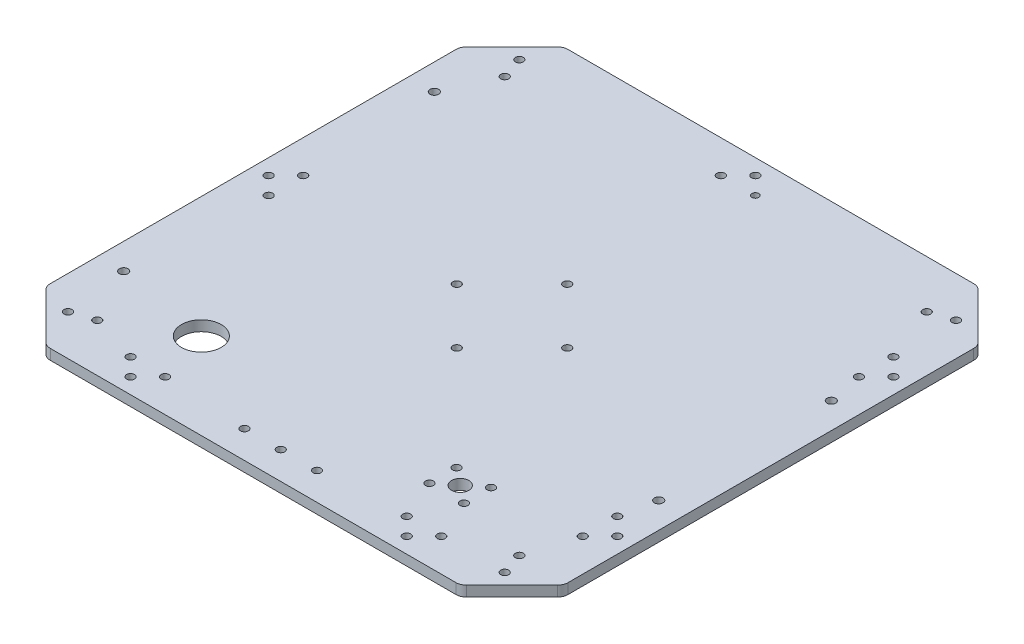
SolidWorks part; units mm, degrees
ref_plane "Plan de face" through (0, 0, 0) normal (0, 0, 1) x (1, 0, 0)
ref_plane "Plan de dessus" through (0, 0, 0) normal (0, 1, 0) x (1, 0, 0)
ref_plane "Plan de droite" through (0, 0, 0) normal (1, 0, 0) x (0, 0, -1)
sketch "Esquisse1" plane through (0, 0, 0) normal (0, 1, 0) x (1, 0, 0)
  line L0 (150, -150) -> (150, 150) construction
  line L1 (150, 150) -> (0, 150) construction
  line L2 (-150, 150) -> (-150, -150) construction
  line L3 (-150, 150) -> (150, 150) construction
  line L4 (150, 0) -> (-150, 0) construction
  line L5 (150, -150) -> (-150, -150) construction
  line L6 (0, 150) -> (0, -150) construction
  line L7 (-150, 0) -> (-150, 120)
  line L8 (0, 150) -> (-120, 150)
  line L9 (-150, 120) -> (-120, 150)
  line L10 (0, 150) -> (120, 150)
  line L11 (150, 0) -> (150, 120)
  line L12 (150, 120) -> (120, 150)
  line L13 (-150, 0) -> (-150, -120)
  line L14 (0, -150) -> (-120, -150)
  line L15 (-120, -150) -> (-150, -120)
  line L16 (150, 0) -> (150, -120)
  line L17 (0, -150) -> (120, -150)
  line L18 (120, -150) -> (150, -120)
  dimension "D1" = 42.4264
  dimension "D2" = 240
extrude "Boss.-Extru.1" add sketch "Esquisse1" along normal blind 6
fillet "Congé3" radius 6 8 edges at (150, 3, -120) (120, 3, -150) (-120, 3, -150) (-150, 3, -120) (-150, 3, 120) (-120, 3, 150) (120, 3, 150) (150, 3, 120)
sketch "Esquisse10" plane through (0, 6, 0) normal (0, 1, 0) x (1, 0, 0)
  line L0 (150, -100) -> (150, 100) construction
  line L1 (150, -117.5147) -> (150, 117.5147) construction
  line L2 (150, 100) -> (-80, 100) construction
  line L3 (-3.3, 0) -> (3.3, 0) construction
  line L4 (150, -100) -> (-80, -100) construction
  circle A0 centre (-80, 100) radius 11.5 construction
  circle A1 centre (-80, -100) radius 11.5
  point P10 (150, 0)
  dimension "D1" = 100
extrude "Enlèv. mat.-Extru.9" cut sketch "Esquisse10" against normal up to next
sketch "Esquisse11" plane through (0, 6, 0) normal (0, 1, 0) x (1, 0, 0)
  line L0 (0, 0) -> (70, 0) construction
  line L1 (70, 100) -> (70, -100) construction
  line L2 (-3.3, 0) -> (3.3, 0) construction
  line L3 (70, -100) -> (80, -100) construction
  line L4 (80, -92.15) -> (80, -107.85) construction
  line L5 (60, -92.15) -> (60, -107.85) construction
  circle A0 centre (70, -100) radius 5
  circle A1 centre (70, 100) radius 5 construction
  circle A2 centre (80, -107.85) radius 2.3
  circle A3 centre (80, -92.15) radius 2.3
  circle A4 centre (60, -92.15) radius 2.3
  circle A5 centre (60, -107.85) radius 2.3
  dimension "D1" = 100
  dimension "D2" = 7.85
  dimension "D3" = 10
extrude "Enlèv. mat.-Extru.10" cut sketch "Esquisse11" against normal up to next
sketch "Esquisse13" plane through (0, 6, 0) normal (0, 1, 0) x (1, 0, 0)
  line L0 (-150, 0) -> (-141, 0) construction
  line L1 (-150, 117.5147) -> (-150, -117.5147) construction
  line L2 (-141, 0) -> (-141, 10) construction
  line L3 (-141, 10) -> (-131, 10) construction
  line L4 (-131, 10) -> (-131, -10) construction
  circle A6 centre (-141, 0) radius 2.3
  circle A7 centre (-131, 10) radius 2.3
  circle A8 centre (-131, -10) radius 2.3
sketch "Esquisse14" plane through (0, 6, 0) normal (0, 1, 0) x (1, 0, 0)
  line L0 (0, -150) -> (-80, -150) construction
  line L1 (-117.5147, -150) -> (117.5147, -150) construction
  line L2 (-80, -150) -> (-80, -141) construction
  line L3 (-80, -141) -> (-70, -141) construction
  line L4 (-70, -141) -> (-70, -131) construction
  line L5 (-70, -131) -> (-90, -131) construction
  circle A0 centre (-80, -141) radius 2.3
  circle A1 centre (-70, -131) radius 2.3
  circle A2 centre (-90, -131) radius 2.3
sketch "Esquisse15" plane through (0, 6, 0) normal (0, 1, 0) x (1, 0, 0)
  line L0 (150, 0) -> (150, 80) construction
  line L1 (150, -117.5147) -> (150, 117.5147) construction
  line L2 (150, 80) -> (141, 80) construction
  line L3 (141, 80) -> (131, 80) construction
  line L4 (131, 80) -> (131, 90) construction
  line L5 (131, 90) -> (131, 70) construction
  circle A0 centre (141, 80) radius 2.3
  circle A1 centre (131, 70) radius 2.3
  circle A2 centre (131, 90) radius 2.3
  dimension "D1" = 9
  dimension "D2" = 10
  dimension "D3" = 20
  dimension "D4" = 10
extrude "Enlèv. mat.-Extru.14" cut sketch "Esquisse15" against normal up to next
mirror "Symétrie13" about plane through (0, 0, 0) normal (0, 0, 1) of "Enlèv. mat.-Extru.14"
extrude "Enlèv. mat.-Extru.15" cut sketch "Esquisse14" against normal up to next
mirror "Symétrie14" about plane through (0, 0, 0) normal (1, 0, 0) of "Enlèv. mat.-Extru.15"
extrude "Enlèv. mat.-Extru.16" cut sketch "Esquisse13" against normal up to next
sketch "Esquisse16" plane through (0, 6, 0) normal (0, 1, 0) x (1, 0, 0)
  line L0 (0, 150) -> (0, 141) construction
  line L1 (117.5147, 150) -> (-117.5147, 150) construction
  line L2 (0, 141) -> (0, 131) construction
  line L3 (0, 131) -> (10, 131) construction
  line L4 (10, 131) -> (-10, 131) construction
  circle A0 centre (0, 141) radius 2.3
  circle A1 centre (10, 131) radius 2
  circle A2 centre (-10, 131) radius 2.3
  dimension "D1" = 9
  dimension "D2" = 10
  dimension "D3" = 10
  dimension "D4" = 20
extrude "Enlèv. mat.-Extru.17" cut sketch "Esquisse16" against normal up to next
sketch "Esquisse17" plane through (0, 6, 0) normal (0, 1, 0) x (1, 0, 0)
  line L0 (135, -135) -> (128.636, -128.636) construction
  line L1 (121.7574, -148.2426) -> (148.2426, -121.7574) construction
  line L2 (128.636, -128.636) -> (126.5147, -130.7574) construction
  line L3 (126.5147, -130.7574) -> (128.636, -128.636) construction
  line L4 (128.636, -128.636) -> (120.1508, -120.1508) construction
  line L5 (120.1508, -120.1508) -> (122.2721, -118.0294) construction
  line L6 (135, 135) -> (128.636, 128.636) construction
  line L7 (148.2426, 121.7574) -> (121.7574, 148.2426) construction
  line L8 (128.636, 128.636) -> (126.5147, 130.7574) construction
  line L9 (126.5147, 130.7574) -> (128.636, 128.636) construction
  line L10 (128.636, 128.636) -> (120.1508, 120.1508) construction
  line L11 (120.1508, 120.1508) -> (122.2721, 118.0294) construction
  line L12 (-135, -135) -> (-128.636, -128.636) construction
  line L13 (-148.2426, -121.7574) -> (-121.7574, -148.2426) construction
  line L14 (-128.636, -128.636) -> (-126.5147, -130.7574) construction
  line L15 (-126.5147, -130.7574) -> (-128.636, -128.636) construction
  line L16 (-128.636, -128.636) -> (-120.1508, -120.1508) construction
  line L17 (-120.1508, -120.1508) -> (-122.2721, -118.0294) construction
  line L18 (-128.636, -128.636) -> (-130.7574, -126.5147) construction
  line L19 (-120.1508, -120.1508) -> (-118.0294, -122.2721) construction
  line L20 (128.636, -128.636) -> (130.7574, -126.5147) construction
  line L21 (120.1508, -120.1508) -> (118.0294, -122.2721) construction
  line L22 (128.636, 128.636) -> (130.7574, 126.5147) construction
  line L23 (120.1508, 120.1508) -> (118.0294, 122.2721) construction
  line L24 (-135, 135) -> (-128.636, 128.636) construction
  line L25 (-121.7574, 148.2426) -> (-148.2426, 121.7574) construction
  line L26 (-128.636, 128.636) -> (-130.7574, 126.5147) construction
  line L27 (-128.636, 128.636) -> (-120.1508, 120.1508) construction
  line L28 (-120.1508, 120.1508) -> (-118.0294, 122.2721) construction
  line L29 (-128.636, 128.636) -> (-126.5147, 130.7574) construction
  line L30 (-120.1508, 120.1508) -> (-122.2721, 118.0294) construction
  circle A2 centre (126.5147, 130.7574) radius 2.3 construction
  circle A4 centre (-122.2721, -118.0294) radius 2.3 construction
  circle A5 centre (-126.5147, -130.7574) radius 2.3 construction
  circle A6 centre (130.7574, -126.5147) radius 2.3 construction
  circle A7 centre (118.0294, -122.2721) radius 2.3 construction
  circle A8 centre (-130.7574, -126.5147) radius 2.3
  circle A9 centre (-118.0294, -122.2721) radius 2.3
  circle A10 centre (126.5147, -130.7574) radius 2.3
  circle A11 centre (122.2721, -118.0294) radius 2.3
  circle A12 centre (118.0294, 122.2721) radius 2.3
  circle A13 centre (130.7574, 126.5147) radius 2.3
  circle A14 centre (-118.0294, 122.2721) radius 2.3 construction
  circle A15 centre (-130.7574, 126.5147) radius 2 construction
  circle A16 centre (-126.5147, 130.7574) radius 2.3
  circle A17 centre (-122.2721, 118.0294) radius 2.3
  dimension "D5" = 3
  dimension "D9" = 9
  dimension "D13" = 3
  dimension "D15" = 9
  dimension "D19" = 3
  dimension "D1" = 12
  dimension "D2" = 9
  dimension "D3" = 3
  dimension "D4" = 3
  dimension "D6" = 3
  dimension "D7" = 12
  dimension "D8" = 9
  dimension "D10" = 3
  dimension "D11" = 3
  dimension "D12" = 12
  dimension "D14" = 3
  dimension "D16" = 3
  dimension "D17" = 12
  dimension "D18" = 3
extrude "Enlèv. mat.-Extru.18" cut sketch "Esquisse17" against normal up to next
sketch "Esquisse18" plane through (0, 6, 0) normal (0, 1, 0) x (1, 0, 0)
  circle A0 centre (0, 0) radius 32 construction
  circle A1 centre (0, -32) radius 2.3
  circle A2 centre (32, 0) radius 2.3
  circle A3 centre (-32, 0) radius 2.3
  circle A4 centre (0, 32) radius 2.3
extrude "Enlèv. mat.-Extru.19" cut sketch "Esquisse18" against normal up to next
sketch "Esquisse20" plane through (0, 6, 0) normal (0, 1, 0) x (1, 0, 0)
  line L0 (-150, 0) -> (-135, 0) construction
  line L1 (-150, 117.5147) -> (-150, -117.5147) construction
  line L2 (-135, 0) -> (-135, -90) construction
  line L3 (-135, 0) -> (-135, 90) construction
  line L5 (135, 0) -> (135, 50) construction
  line L6 (135, 0) -> (135, -50) construction
  line L7 (150, 0) -> (135, 0) construction
  circle A0 centre (-135, -90) radius 2.5
  circle A1 centre (-135, 90) radius 2.5
  circle A2 centre (135, 50) radius 2.5
  circle A3 centre (135, -50) radius 2.5
  point P18 (0, 0)
  point P19 (0, 0)
  point P20 (0, 0)
  dimension "D1" = 90
  dimension "D2" = 90
  dimension "D3" = 50
  dimension "D4" = 50
extrude "Enlèv. mat.-Extru.21" cut sketch "Esquisse20" against normal up to next
sketch "Esquisse21" plane through (0, 6, 0) normal (0, 1, 0) x (1, 0, 0)
  line L0 (0, -150) -> (0, -134) construction
  line L1 (-117.5147, -150) -> (117.5147, -150) construction
  line L2 (-21, -134) -> (21, -134) construction
  circle A0 centre (0, -134) radius 2.3
  circle A1 centre (21, -134) radius 2.3
  circle A2 centre (-21, -134) radius 2.3
  dimension "D1" = 16
  dimension "D2" = 21
extrude "Enlèv. mat.-Extru.22" cut sketch "Esquisse21" against normal up to next
